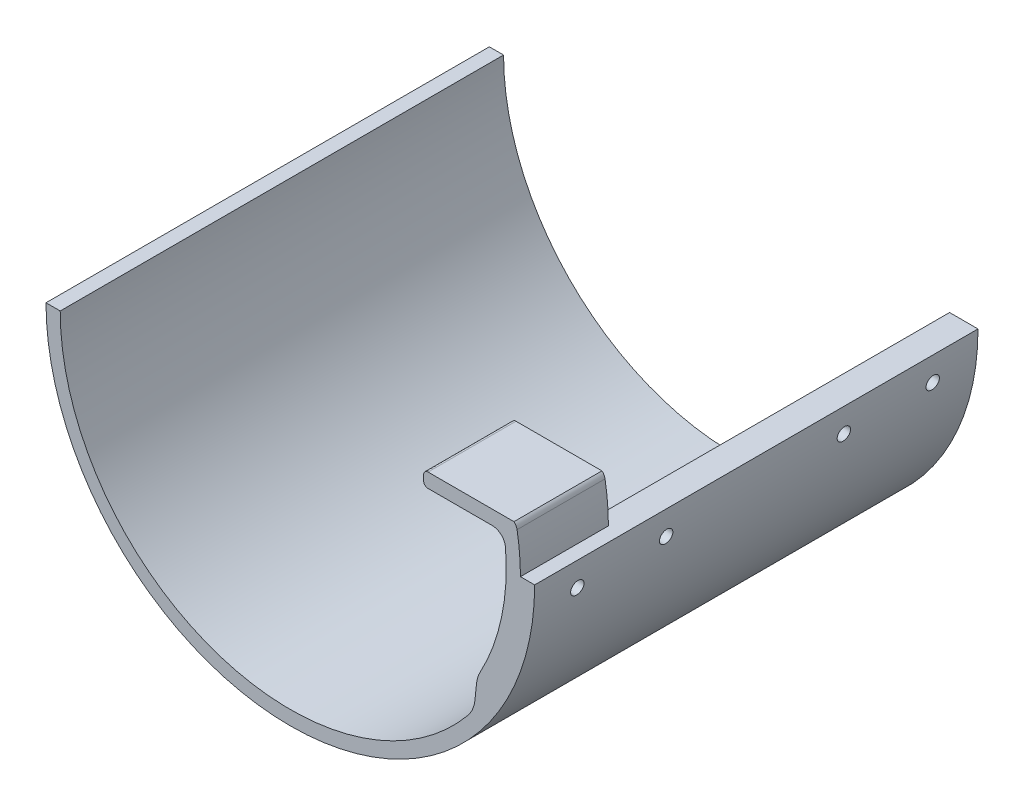
SolidWorks part; units mm, degrees
ref_plane "前视基准面" through (0, 0, 0) normal (0, 0, 1) x (1, 0, 0)
ref_plane "上视基准面" through (0, 0, 0) normal (0, 1, 0) x (1, 0, 0)
ref_plane "右视基准面" through (0, 0, 0) normal (1, 0, 0) x (0, 0, -1)
other "Configuration Table"
sketch "草图1" plane through (0, 0, 0) normal (0, 0, 1) x (1, 0, 0)
  line L0 (-55, 0) -> (-51.8, 0)
  line L1 (51.8, 0) -> (55, 0)
  line L2 (-51.8, 0) -> (51.8, 0) construction
  line L5 (41.9103, -25.796) -> (41.5651, -29.1691)
  line L6 (0, 0) -> (0, 10) construction
  line L7 (0, 10) -> (31, 10) construction
  line L9 (30, 9) -> (30, 7.8)
  line L10 (31, 6.8) -> (45.4414, 6.8)
  line L11 (31, 10) -> (50.344, 10)
  arc A0 (-55, 0) -> (55, 0) centre (0, 0) ccw
  arc A1 (-51.8, 0) -> (40.008, -32.9029) centre (0, 0) ccw
  arc A2 (51.0485, 8.7916) -> (51.8, 0) centre (0, 0) cw
  arc A3 (42.7207, -23.1711) -> (48.431, 4.05) centre (0, 0) ccw
  arc A4 (41.5651, -29.1691) -> (40.008, -32.9029) centre (34.6015, -28.4566) cw
  arc A5 (41.9103, -25.796) -> (42.7207, -23.1711) centre (48.8739, -26.5085) cw
  arc A6 (48.431, 4.05) -> (45.4414, 6.8) centre (45.4414, 3.8) ccw
  arc A7 (51.0485, 8.7916) -> (50.344, 10) centre (49.0775, 8.4521) ccw
  arc A8 (31, 6.8) -> (30, 7.8) centre (31, 7.8) cw
  arc A9 (30, 9) -> (31, 10) centre (31, 9) cw
  point P16 (42.0579, -24.3536)
  point P25 (52.0183, 10)
  point P28 (30, 6.8)
  point P31 (30.5845, 10)
  dimension "D1" = 110
  dimension "D2" = 103.6
  dimension "D3" = 97.2
  dimension "D6" = 7
  dimension "D9" = 3
  dimension "D10" = 2
  dimension "D11" = 1
  dimension "D12" = 1
  dimension "D14" = 51.8
  dimension "D5" = 31
  dimension "D7" = 3.2
  dimension "D8" = 21.4339
  dimension "D13" = 10
extrude "凸台-拉伸1" add sketch "草图1" along normal blind 99.8
sketch "草图4" plane through (0, 0, 99.8) normal (0, 0, 1) x (1, 0, 0)
  line L0 (55, 0) -> (0, 0)
  line L1 (0, 0) -> (50.017, 22.8758)
  arc A0 (55, 0) -> (50.017, 22.8758) centre (0, 0) ccw
sketch "草图5" plane through (0, 0, 0) normal (0, 0, -1) x (-1, 0, 0)
  line L0 (0, 0) -> (0, -5.5)
  line L1 (0, -5.5) -> (54.3615, -5.5)
  line L2 (0, 0) -> (54.3615, -5.5) construction
  line L3 (0, 0) -> (5.5, 54.3615) construction
  line L4 (0, 0) -> (0, 54.639) construction
  line L5 (0, 0) -> (-54.3615, -5.5) construction
  line L6 (0, 0) -> (-5.5, 54.3615) construction
  circle A0 centre (0, 0) radius 54.639
  dimension "D1" = 5.5
  dimension "D2" = 90
ref_plane "基准面1" through (0, 0, 0) normal (-0.9949, 0.1007, 0) x (0.1007, 0.9949, 0)
sketch "草图7" plane through (0, 0, 0) normal (-0.9949, 0.1007, 0) x (0.1007, 0.9949, 0)
  line L0 (-5.5363, -99.8) -> (-5.5363, 0) construction
  line L1 (-55, -99.8) -> (5.5363, -99.8) construction
  line L2 (-0.1363, 0) -> (-0.1363, -99.8) construction
  line L3 (54.639, 0) -> (-54.639, 0) construction
  line L4 (-5.4721, 0) -> (-10.9441, 0) construction
  circle A0 centre (-0.1363, -9.9) radius 1.5
  circle A1 centre (-0.1363, -29.9) radius 1.5
  circle A2 centre (-0.1363, -69.9) radius 1.5
  circle A3 centre (-0.1363, -89.9) radius 1.5
  dimension "D1" = 3
  dimension "D2" = 3
  dimension "D3" = 3
  dimension "D4" = 3
  dimension "D5" = 5.4
  dimension "D6" = 9.9
  dimension "D7" = 20
  dimension "D8" = 9.9
  dimension "D9" = 20
extrude "切除-拉伸6" cut sketch "草图7" against normal blind 80
sketch "草图8" plane through (0, 0, 0) normal (0, 0, -1) x (-1, 0, 0)
  line L0 (-55, 0) -> (0, 0) construction
  line L1 (-50.017, 22.8758) -> (0, 0)
  line L2 (0, 0) -> (-55, 0)
  arc A0 (-50.017, 22.8758) -> (-55, 0) centre (0, 0) ccw
extrude "切除-拉伸7" cut sketch "草图8" against normal blind 80
